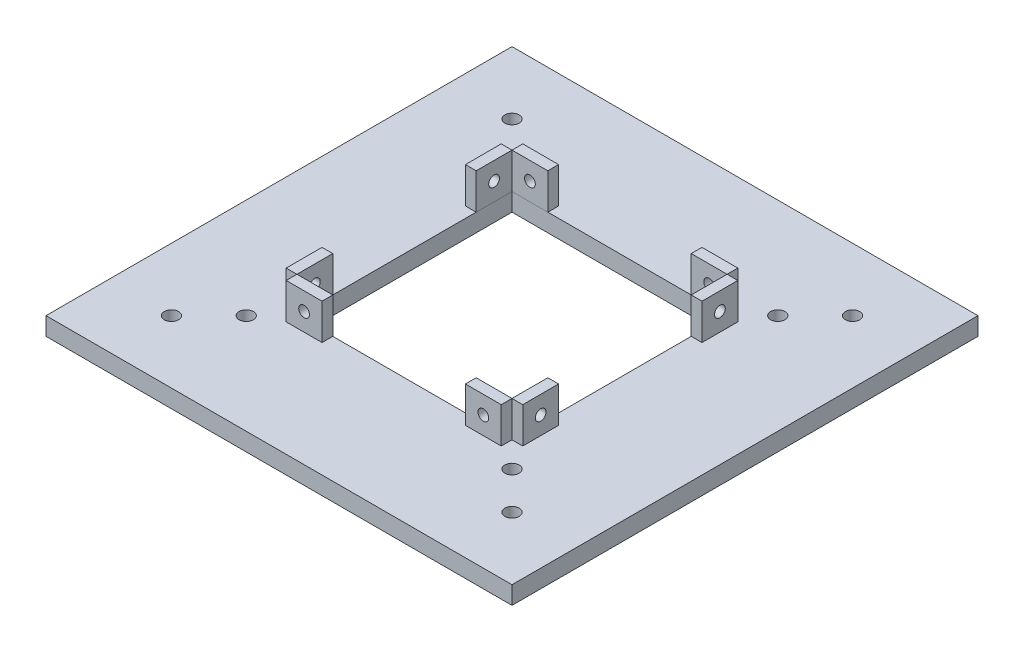
SolidWorks part; units mm, degrees
ref_plane "Front Plane" through (0, 0, 0) normal (0, 0, 1) x (1, 0, 0)
ref_plane "Top Plane" through (0, 0, 0) normal (0, 1, 0) x (1, 0, 0)
ref_plane "Right Plane" through (0, 0, 0) normal (1, 0, 0) x (0, 0, -1)
sketch "Sketch1" plane through (0, 0, 0) normal (0, 1, 0) x (1, 0, 0)
  line L0 (-65, 65) -> (65, 65)
  line L1 (-65, 65) -> (-65, -65)
  line L2 (-65, -65) -> (65, -65)
  line L3 (65, 65) -> (65, -65)
  line L4 (-65, 65) -> (-30, 30)
  line L5 (-30, 30) -> (30, 30)
  line L6 (-30, 30) -> (-30, -30)
  line L7 (-30, -30) -> (30, -30)
  line L8 (30, 30) -> (30, -30)
  line L9 (30, 30) -> (65, 65)
  line L10 (30, -30) -> (65, -65)
  line L11 (-30, -30) -> (-65, -65)
  circle A0 centre (-47.5, 47.5) radius 2
  circle A1 centre (-47.5, -47.5) radius 2
  circle A2 centre (47.5, -47.5) radius 2
  circle A3 centre (47.5, 47.5) radius 2
  circle A4 centre (37.0711, -37.0711) radius 2
  circle A5 centre (-37.0711, -37.0711) radius 2
  circle A6 centre (-37.0711, 37.0711) radius 2
  circle A7 centre (37.0711, 37.0711) radius 2
  dimension "D2" = 4
  dimension "D3" = 4
  dimension "D1" = 130
  dimension "D4" = 10
  dimension "D5" = 10
  dimension "D6" = 10
  dimension "D7" = 10
extrude "Boss-Extrude1" add sketch "Sketch1" along normal blind 5 contours A6 L4 A0 L1 L11 A1 A5 L6 | A7 L9 A3 L0 L4 A0 A6 L5 | A5 L11 A1 L2 L10 A2 A4 L7 | A7 L9 L8 L10 A4 A2 L3 A3
sketch "Sketch2" plane through (0, 5, 0) normal (0, 1, 0) x (1, 0, 0)
  line L33 (-30, 30) -> (-20, 30)
  line L34 (-30, 30) -> (-30, 33)
  line L35 (-30, 33) -> (-20, 33)
  line L36 (-20, 30) -> (-20, 33)
  line L37 (-30, 30) -> (-33, 30)
  line L38 (-30, 30) -> (-30, 20)
  line L39 (-30, 20) -> (-33, 20)
  line L40 (-33, 30) -> (-33, 20)
  line L41 (30, 30) -> (20, 30)
  line L42 (30, 30) -> (30, 33)
  line L43 (30, 33) -> (20, 33)
  line L44 (20, 30) -> (20, 33)
  line L45 (30, 30) -> (33, 30)
  line L46 (30, 30) -> (30, 20)
  line L47 (30, 20) -> (33, 20)
  line L48 (33, 30) -> (33, 20)
  line L49 (30, -30) -> (33, -30)
  line L50 (30, -30) -> (30, -20)
  line L51 (30, -20) -> (33, -20)
  line L52 (33, -30) -> (33, -20)
  line L53 (30, -30) -> (20, -30)
  line L54 (30, -30) -> (30, -33)
  line L55 (30, -33) -> (20, -33)
  line L56 (20, -30) -> (20, -33)
  line L57 (-30, -30) -> (-20, -30)
  line L58 (-30, -30) -> (-30, -33)
  line L59 (-30, -33) -> (-20, -33)
  line L60 (-20, -30) -> (-20, -33)
  line L61 (-30, -30) -> (-33, -30)
  line L62 (-30, -30) -> (-30, -20)
  line L63 (-30, -20) -> (-33, -20)
  line L64 (-33, -30) -> (-33, -20)
  line M29 (30, 30) -> (30, -30)
  line M30 (30, -30) -> (-30, -30)
  line M31 (-30, -30) -> (-30, 30)
  line M32 (-30, 30) -> (30, 30)
  dimension "D1" = 3
  dimension "D2" = 10
  dimension "D3" = 3
  dimension "D4" = 10
  dimension "D5" = 10
  dimension "D6" = 3
  dimension "D7" = 3
  dimension "D8" = 10
  dimension "D9" = 10
  dimension "D10" = 3
  dimension "D11" = 10
  dimension "D12" = 3
  dimension "D13" = 10
  dimension "D14" = 3
  dimension "D15" = 3
  dimension "D16" = 10
extrude "Boss-Extrude10" add sketch "Sketch2" along normal blind 10 separate body contours L37 L40 L39 M31 | L36 L35 L34 M32 | L44 L42 L43 M32 | L56 L55 L54 M30 | L48 L45 L47 M29 | L60 L58 L59 M30 | L64 L61 L63 M31 | L49 L52 L51 M29
sketch "Sketch4" plane through (-33, 0, 0) normal (-1, 0, 0) x (0, 0, 1)
  circle A0 centre (-25, 10) radius 1.5
  circle A1 centre (25, 10) radius 1.5
extrude "Cut-Extrude1" cut sketch "Sketch4" against normal blind 82
sketch "Sketch5" plane through (0, 0, -33) normal (0, 0, -1) x (-1, 0, 0)
  circle A0 centre (-25, 10) radius 1.5
  circle A1 centre (25, 10) radius 1.5
extrude "Cut-Extrude2" cut sketch "Sketch5" against normal blind 82
